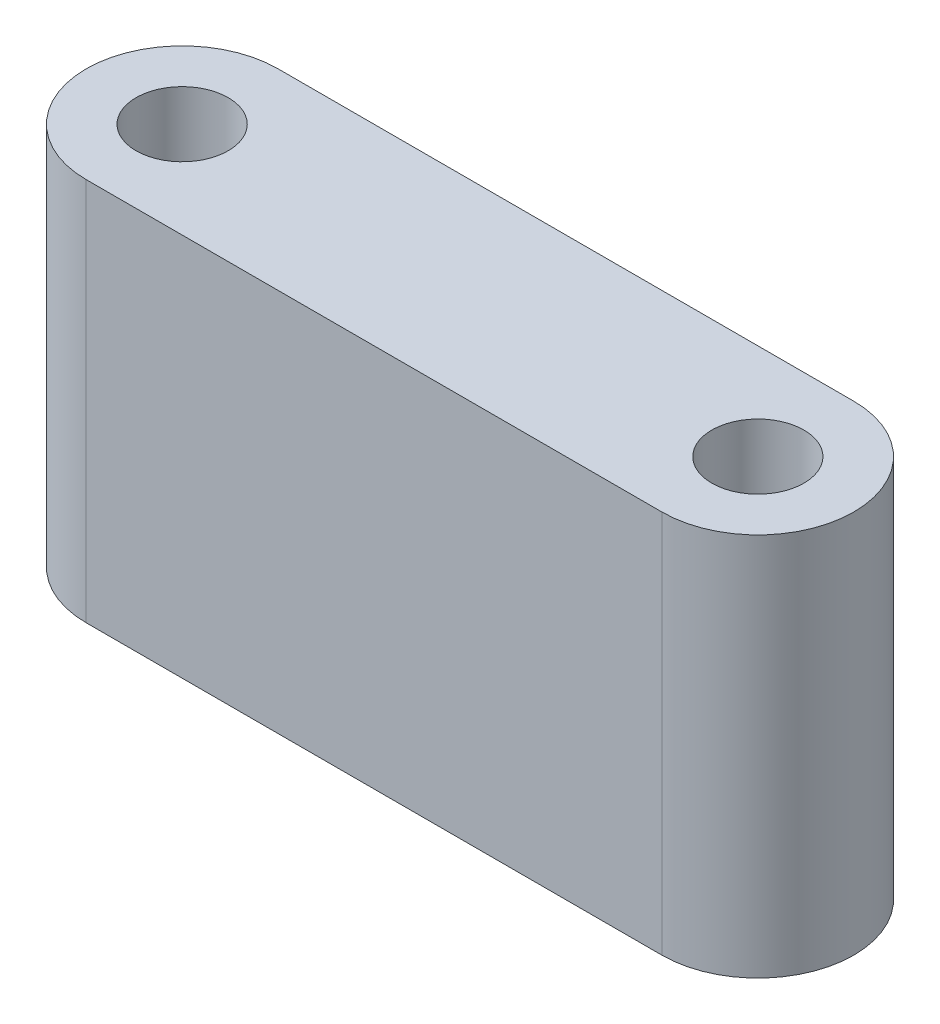
SolidWorks part; units mm, degrees
ref_plane "前视基准面" through (0, 0, 0) normal (0, 0, 1) x (1, 0, 0)
ref_plane "上视基准面" through (0, 0, 0) normal (0, 1, 0) x (1, 0, 0)
ref_plane "右视基准面" through (0, 0, 0) normal (1, 0, 0) x (0, 0, -1)
sketch "草图1" plane through (0, 0, 0) normal (0, 1, 0) x (1, 0, 0)
  line L0 (0, 0) -> (30, 0) construction
  line L1 (0, 5) -> (30, 5)
  line L2 (0, -5) -> (30, -5)
  arc A0 (0, 5) -> (0, -5) centre (0, 0) ccw
  arc A1 (30, -5) -> (30, 5) centre (30, 0) ccw
  circle A2 centre (0, 0) radius 2.4
  circle A3 centre (30, 0) radius 2.4
  point P3 (15, 0)
  dimension "D2" = 4.8
  dimension "D3" = 5
  dimension "D1" = 30
extrude "凸台-拉伸1" add sketch "草图1" along normal blind 20
